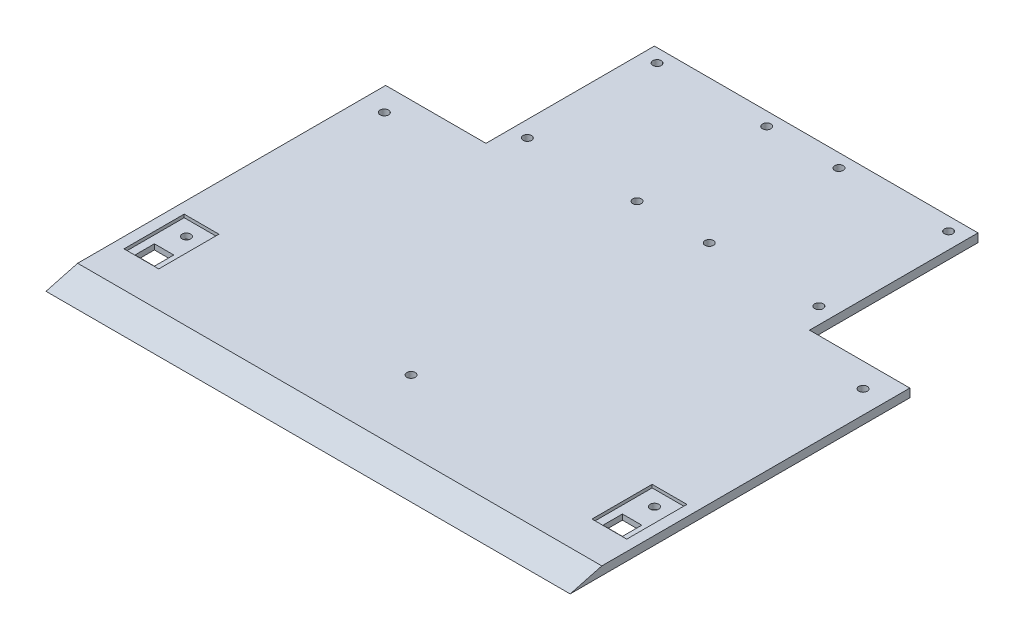
SolidWorks part; units mm, degrees
ref_plane "Alzado" through (0, 0, 0) normal (0, 0, 1) x (1, 0, 0)
ref_plane "Planta" through (0, 0, 0) normal (0, 1, 0) x (1, 0, 0)
ref_plane "Vista lateral" through (0, 0, 0) normal (1, 0, 0) x (0, 0, -1)
sketch "Croquis1" plane through (0, 0, 0) normal (1, 0, 0) x (0, 0, -1)
  line L0 (0, 0) -> (190, 0)
  line L1 (190, 0) -> (190, 3.17)
  line L2 (190, 3.17) -> (11.8306, 3.17)
  line L3 (0, 0) -> (11.8306, 3.17)
  dimension "D1" = 190
  dimension "D2" = 3.17
  dimension "D3" = 165
extrude "Saliente-Extruir1" add sketch "Croquis1" along normal blind 196
sketch "Croquis2" plane through (0, 0, 0) normal (0, -1, 0) x (-1, 0, 0)
  line L0 (0, 190) -> (0, 11.8306) construction
  line L1 (0, 127.0101) -> (-37.5, 127.0101)
  line L2 (0, 127.0101) -> (0, 190)
  line L3 (0, 190) -> (-37.5, 190)
  line L4 (-37.5, 127.0101) -> (-37.5, 190)
  line L5 (0, 127.0101) -> (-37.5, 190) construction
  line L6 (0, 190) -> (-37.5, 127.0101) construction
  line L7 (-196, 127.0101) -> (0, 127.0101) construction
  line L8 (-196, 190) -> (0, 190) construction
  line L9 (-37.5, 131.5) -> (-37.5, 190) construction
  point P4 (-18.75, 158.5051)
extrude "Cortar-Extruir1" cut sketch "Croquis2" against normal up to next
ref_plane "Plano1" through (98, 0, 0) normal (-1, 0, 0) x (0, 0, 1)
mirror "Simetría1" about plane through (98, 0, 0) normal (-1, 0, 0) of "Cortar-Extruir1"
sketch "Croquis3" plane through (0, 3.17, 0) normal (0, 1, 0) x (1, 0, 0)
  line L0 (196, 0) -> (0, 0) construction
  line L1 (4, 47.66) -> (17, 47.66)
  line L2 (4, 47.66) -> (4, 25.16)
  line L3 (4, 25.16) -> (17, 25.16)
  line L4 (17, 47.66) -> (17, 25.16)
  line L5 (4, 47.66) -> (17, 25.16) construction
  line L6 (4, 25.16) -> (17, 47.66) construction
  line L7 (0, 127.0101) -> (0, 11.8306) construction
  point P4 (10.5, 36.41)
  dimension "D1" = 25.16
  dimension "D2" = 22.5
  dimension "D3" = 13
  dimension "D4" = 4
extrude "Cortar-Extruir2" cut sketch "Croquis3" against normal blind 1.17
sketch "Croquis4" plane through (0, 2, 0) normal (0, 1, 0) x (1, 0, 0)
  line L0 (10.5, 25.16) -> (10.5, 26.41) construction
  line L1 (4, 25.16) -> (17, 25.16) construction
  line L2 (4, 26.41) -> (17, 26.41) construction
  line L3 (4, 47.66) -> (4, 25.16) construction
  line L4 (17, 25.16) -> (17, 47.66) construction
  line L5 (10.5, 26.41) -> (10.5, 33.66) construction
  line L6 (10.5, 30.035) -> (6.875, 30.035) construction
  line L7 (10.5, 30.035) -> (14.125, 30.035) construction
  line L8 (6.875, 30.035) -> (6.875, 26.41) construction
  line L9 (14.125, 30.035) -> (14.125, 33.66) construction
  dimension "D1" = 1.25
  dimension "D2" = 7.25
  dimension "D3" = 3.625
  dimension "D4" = 3.625
sketch "Croquis5" plane through (0, 2, 0) normal (0, 1, 0) x (1, 0, 0)
  line L1 (6.875, 26.41) -> (14.125, 26.41)
  line L2 (6.875, 26.41) -> (6.875, 33.66)
  line L3 (6.875, 33.66) -> (14.125, 33.66)
  line L4 (14.125, 26.41) -> (14.125, 33.66)
  line L5 (6.875, 26.41) -> (14.125, 33.66) construction
  line L6 (6.875, 33.66) -> (14.125, 26.41) construction
  point P4 (10.5, 30.035)
extrude "Cortar-Extruir3" cut sketch "Croquis5" against normal up to next
sketch "Croquis6" plane through (0, 2, 0) normal (0, 1, 0) x (1, 0, 0)
  line L0 (10.5, 47.66) -> (10.5, 46.41) construction
  line L1 (17, 47.66) -> (4, 47.66) construction
  line L2 (10.5, 46.41) -> (17, 46.41) construction
  line L3 (17, 25.16) -> (17, 47.66) construction
  line L4 (17, 46.41) -> (4, 46.41) construction
  line L5 (4, 47.66) -> (4, 25.16) construction
  circle A0 centre (10.5, 42.01) radius 1.6
  dimension "D2" = 3.2
  dimension "D1" = 1.25
  dimension "D3" = 4.4
extrude "Cortar-Extruir4" cut sketch "Croquis6" against normal up to next
mirror "Simetría2" about plane through (98, 0, 0) normal (-1, 0, 0) of "Cortar-Extruir2", "Cortar-Extruir4", "Cortar-Extruir3"
sketch "Sketch1" plane through (0, 3.17, 0) normal (0, 1, 0) x (1, 0, 0)
  circle A0 centre (8.5, 118.0101) radius 1.585
  circle A1 centre (187.5, 118.0101) radius 1.585
extrude "Cut-Extrude1" cut sketch "Sketch1" against normal up to next
sketch "Sketch2" plane through (0, 3.17, 0) normal (0, 1, 0) x (1, 0, 0)
  circle A0 centre (98.5, 38.0101) radius 1.585
extrude "Cut-Extrude2" cut sketch "Sketch2" against normal up to next
sketch "Sketch3" plane through (0, 3.17, 0) normal (0, 1, 0) x (1, 0, 0)
  circle A0 centre (43.5, 185) radius 1.5799
  circle A1 centre (84.5, 185) radius 1.585
  circle A2 centre (152.5, 185) radius 1.585
  circle A3 centre (111.5, 185) radius 1.585
  circle A4 centre (111.5, 136.5) radius 1.585
  circle A5 centre (152.5, 136.5) radius 1.585
  circle A6 centre (84.5, 136.5) radius 1.585
  circle A7 centre (43.5, 136.5) radius 1.585
extrude "Cut-Extrude3" cut sketch "Sketch3" against normal up to next
